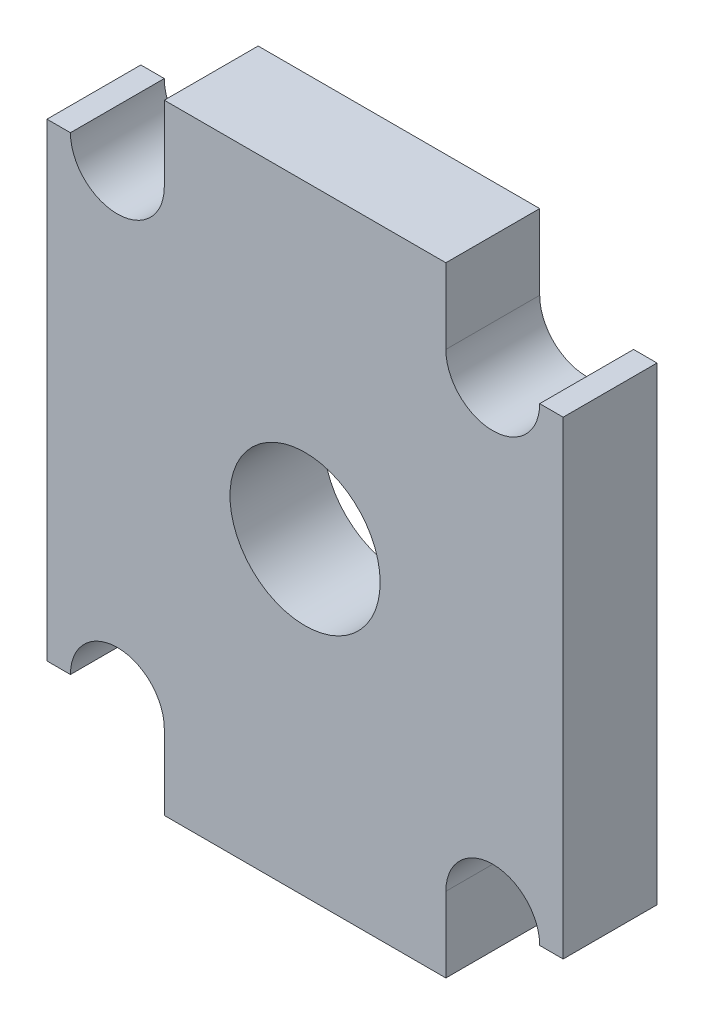
SolidWorks part; units mm, degrees
material "Thornel VCB-20 Carbon Cloth"
ref_plane "Front Plane" through (0, 0, 0) normal (0, 0, 1) x (1, 0, 0)
ref_plane "Top Plane" through (0, 0, 0) normal (0, 1, 0) x (1, 0, 0)
ref_plane "Right Plane" through (0, 0, 0) normal (1, 0, 0) x (0, 0, -1)
sketch "Sketch1" plane through (0, 0, 0) normal (0, 0, 1) x (1, 0, 0)
  line L0 (115.05, 10) -> (115.05, 11.6)
  line L1 (115.05, -1.6) -> (121.05, -1.6)
  line L2 (121.05, -1.6) -> (121.05, 0)
  line L3 (123.55, 0) -> (123.05, 0)
  line L4 (123.55, 0) -> (123.55, 10)
  line L5 (123.55, 10) -> (123.05, 10)
  line L6 (121.05, 10) -> (121.05, 11.6)
  line L7 (121.05, 11.6) -> (115.05, 11.6)
  line L8 (118.05, 11.6) -> (118.05, -1.6) construction
  line L9 (112.55, 10) -> (113.05, 10)
  line L10 (112.55, 0) -> (112.55, 10)
  line L11 (112.55, 0) -> (113.05, 0)
  line L12 (115.05, -1.6) -> (115.05, 0)
  line L13 (121.05, 0) -> (115.05, 0) construction
  line L14 (118.05, 5) -> (124.4368, 5) construction
  line L15 (126.6366, 0) -> (122.05, 0) construction
  line L16 (115.05, -1.6) -> (121.05, -1.6) construction
  circle A0 centre (118.05, 5) radius 1.6 construction
  circle A1 centre (118.05, 5) radius 1.6
  arc A2 (121.05, 0) -> (123.05, 0) centre (122.05, 0) cw
  arc A3 (121.05, 10) -> (123.05, 10) centre (122.05, 10) ccw
  arc A4 (115.05, 10) -> (113.05, 10) centre (114.05, 10) cw
  arc A5 (115.05, 0) -> (113.05, 0) centre (114.05, 0) ccw
  point P14 (118.05, 0)
  dimension "D2" = 1
  dimension "D1" = 2.5
extrude "Boss-Extrude1" add sketch "Sketch1" along normal blind 2
